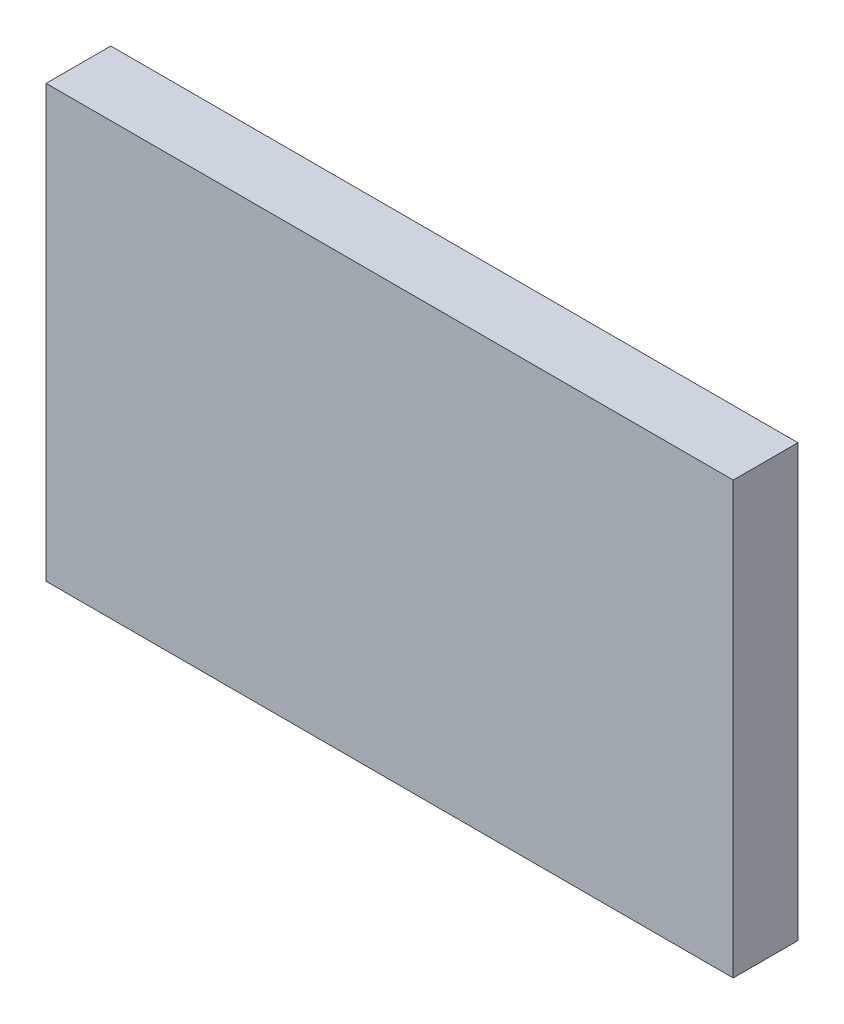
SolidWorks part; units mm, degrees
ref_plane "Plan de face" through (0, 0, 0) normal (0, 0, 1) x (1, 0, 0)
ref_plane "Plan de dessus" through (0, 0, 0) normal (0, 1, 0) x (1, 0, 0)
ref_plane "Plan de droite" through (0, 0, 0) normal (1, 0, 0) x (0, 0, -1)
sketch "Esquisse1" plane through (0, 0, 0) normal (0, 0, 1) x (1, 0, 0)
  line L0 (-5.3623, 3.3655) -> (5.2616, 3.3655)
  line L1 (5.2616, 3.3655) -> (5.2616, -3.302)
  line L2 (5.2616, -3.302) -> (-5.3623, -3.302)
  line L3 (-5.3623, -3.302) -> (-5.3623, 3.3655)
extrude "Component_Outline" add sketch "Esquisse1" along normal blind 1 separate body
sketch3d "Esquisse3D1"
  line L0 (0, 0, 0) -> (1, 0, 0)
  line L1 (0, 0, 0) -> (0, 1, 0)
  line L2 (0, 0, 0) -> (0, 0, 1)
  point P0 (0, 0, 0)
